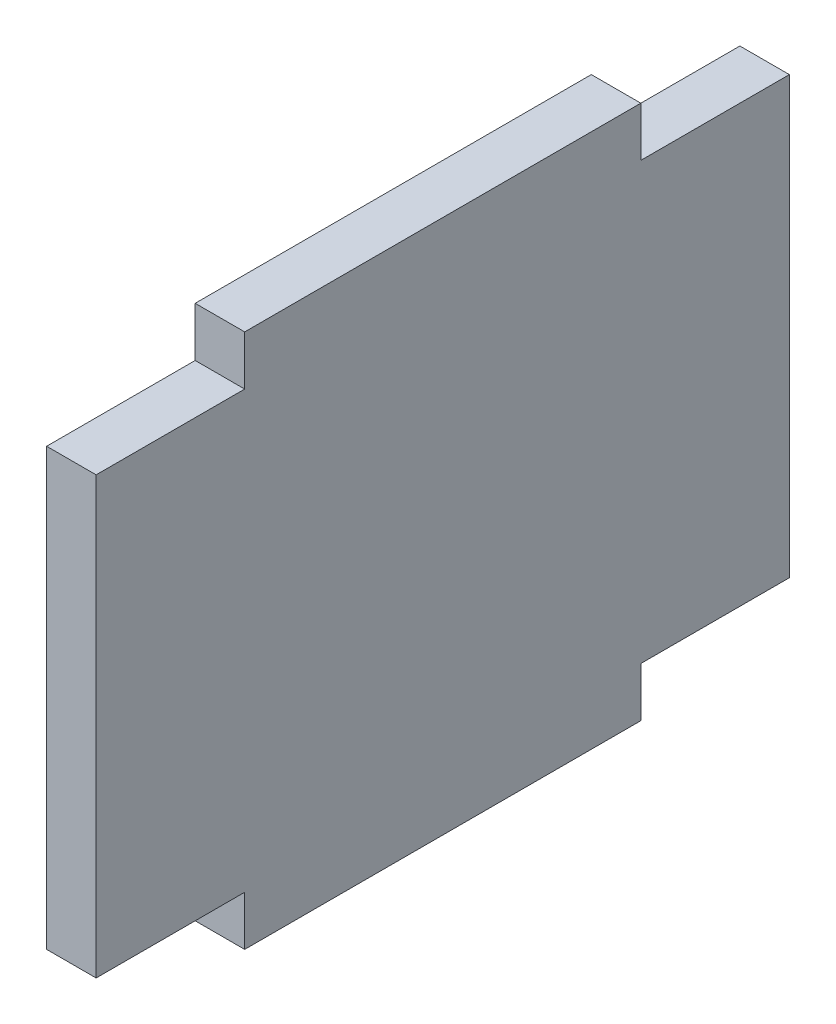
SolidWorks part; units mm, degrees
material "Maple"
ref_plane "Front Plane" through (0, 0, 0) normal (0, 0, 1) x (1, 0, 0)
ref_plane "Top Plane" through (0, 0, 0) normal (0, 1, 0) x (1, 0, 0)
ref_plane "Right Plane" through (0, 0, 0) normal (1, 0, 0) x (0, 0, -1)
sketch "Sketch1" plane through (0, 0, 0) normal (1, 0, 0) x (0, 0, -1)
  line L0 (17.5, 0) -> (-17.5, 0) construction
  line L1 (-17.5, -11) -> (17.5, -11) construction
  line L2 (-17.5, -11) -> (-17.5, 11)
  line L3 (-17.5, 11) -> (17.5, 11) construction
  line L4 (17.5, -11) -> (17.5, 11)
  line L5 (-17.5, -11) -> (17.5, 11) construction
  line L6 (-17.5, 11) -> (17.5, -11) construction
  line L7 (-10, 13.5) -> (10, 13.5)
  line L8 (-10, 13.5) -> (-10, 11)
  line L9 (-10, 11) -> (10, 11) construction
  line L10 (10, 13.5) -> (10, 11)
  line L11 (-10, 13.5) -> (10, 11) construction
  line L12 (-10, 11) -> (10, 13.5) construction
  line L13 (-10, -11) -> (10, -11) construction
  line L14 (10, -13.5) -> (10, -11)
  line L15 (-10, -13.5) -> (10, -13.5)
  line L16 (-10, -13.5) -> (-10, -11)
  line L17 (-17.5, -11) -> (-10, -11)
  line L18 (10, -11) -> (17.5, -11)
  line L19 (17.5, 11) -> (10, 11)
  line L20 (-10, 11) -> (-17.5, 11)
  point P0 (0, 0)
  point P6 (0, 12.25)
  dimension "D1" = 35
  dimension "D2" = 22
  dimension "D3" = 20
  dimension "D4" = 2.5
extrude "Boss-Extrude1" add sketch "Sketch1" along normal mid plane 2.5
